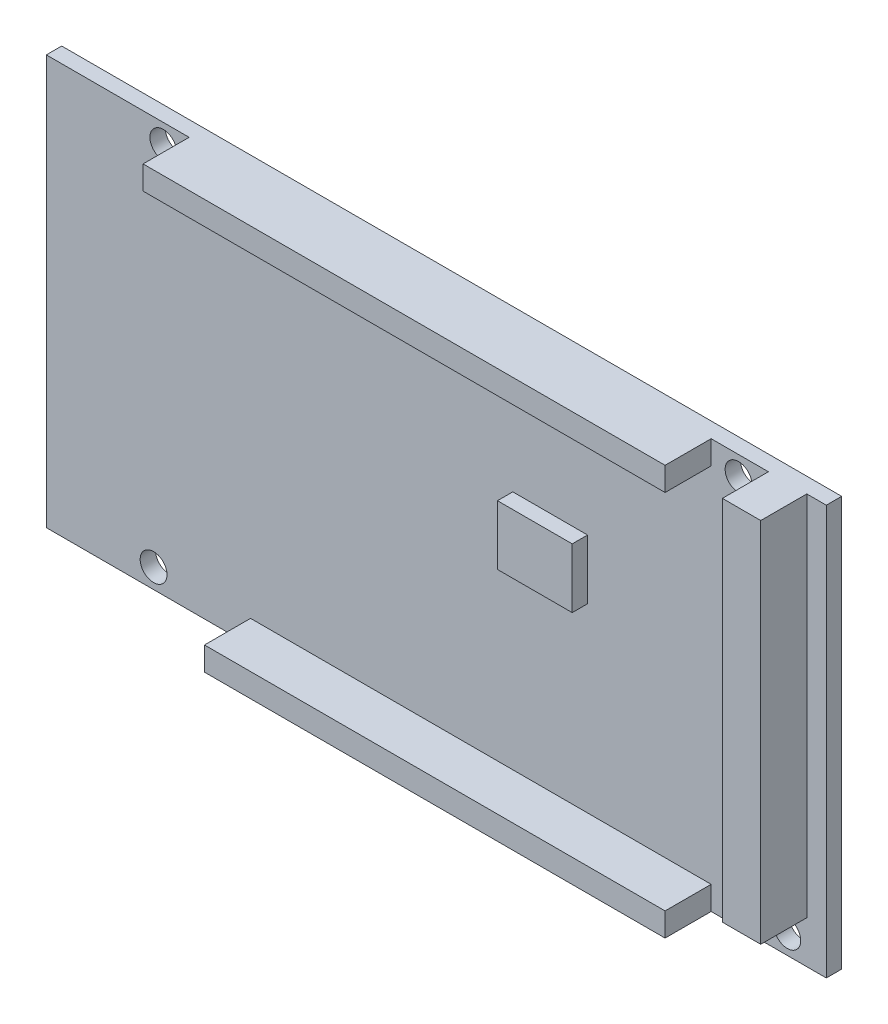
SolidWorks part; units mm, degrees
ref_plane "前视基准面" through (0, 0, 0) normal (0, 0, 1) x (1, 0, 0)
ref_plane "上视基准面" through (0, 0, 0) normal (0, 1, 0) x (1, 0, 0)
ref_plane "右视基准面" through (0, 0, 0) normal (1, 0, 0) x (0, 0, -1)
sketch "草图1" plane through (0, 0, 0) normal (0, 0, 1) x (1, 0, 0)
  line L1 (-50.8, -26.67) -> (50.8, -26.67)
  line L2 (-50.8, -26.67) -> (-50.8, 26.67)
  line L3 (-50.8, 26.67) -> (50.8, 26.67)
  line L4 (50.8, -26.67) -> (50.8, 26.67)
  line L5 (0, 26.67) -> (0, -26.67) construction
  line L6 (-50.8, 0) -> (50.8, 0) construction
  circle A0 centre (-35.56, 24.13) radius 1.75
  circle A1 centre (-36.83, -24.13) radius 1.75
  circle A2 centre (45.72, -24.13) radius 1.75
  circle A3 centre (39.37, 24.13) radius 1.75
  point P0 (0, 0)
  dimension "D3" = 15.24
  dimension "D1" = 101.6
  dimension "D2" = 53.34
  dimension "D4" = 13.97
  dimension "D5" = 2.54
  dimension "D6" = 50.8
  dimension "D7" = 50.8
  dimension "D8" = 2.54
  dimension "D9" = 96.52
  dimension "D10" = 90.17
extrude "凸台-拉伸1" add sketch "草图1" along normal blind 2
sketch "草图2" plane through (0, 0, 2) normal (0, 0, 1) x (1, 0, 0)
  line L0 (50.8, 26.67) -> (-50.8, 26.67) construction
  line L1 (-32.2, 26.67) -> (35.8, 26.67)
  line L2 (-32.2, 26.67) -> (-32.2, 23.6)
  line L3 (-32.2, 23.6) -> (35.8, 23.6)
  line L4 (35.8, 26.67) -> (35.8, 23.6)
  line L5 (-50.8, 26.67) -> (-50.8, -26.67) construction
  line L6 (-50.8, -26.67) -> (50.8, -26.67) construction
  line L7 (-24.2, -26.67) -> (35.8, -26.67)
  line L8 (-24.2, -26.67) -> (-24.2, -23.6)
  line L9 (-24.2, -23.6) -> (35.8, -23.6)
  line L10 (35.8, -26.67) -> (35.8, -23.6)
  line L11 (50.8, -26.67) -> (50.8, 26.67) construction
  line L12 (43.26, 26.67) -> (48.26, 26.67)
  line L13 (43.26, 26.67) -> (43.26, -21.14)
  line L14 (43.26, -21.14) -> (48.26, -21.14)
  line L15 (48.26, 26.67) -> (48.26, -21.14)
  dimension "D1" = 3.07
  dimension "D2" = 68
  dimension "D3" = 18.6
  dimension "D4" = 3.07
  dimension "D5" = 60
  dimension "D6" = 26.6
  dimension "D7" = 47.81
  dimension "D8" = 5
  dimension "D9" = 2.54
extrude "凸台-拉伸2" add sketch "草图2" along normal blind 6
sketch "草图3" plane through (0, 0, 2) normal (0, 0, 1) x (1, 0, 0)
  line L1 (9.9635, 0) -> (19.7006, 0)
  line L2 (9.9635, 0) -> (9.9635, 7.7557)
  line L3 (9.9635, 7.7557) -> (19.7006, 7.7557)
  line L4 (19.7006, 0) -> (19.7006, 7.7557)
extrude "凸台-拉伸3" add sketch "草图3" along normal blind 2
